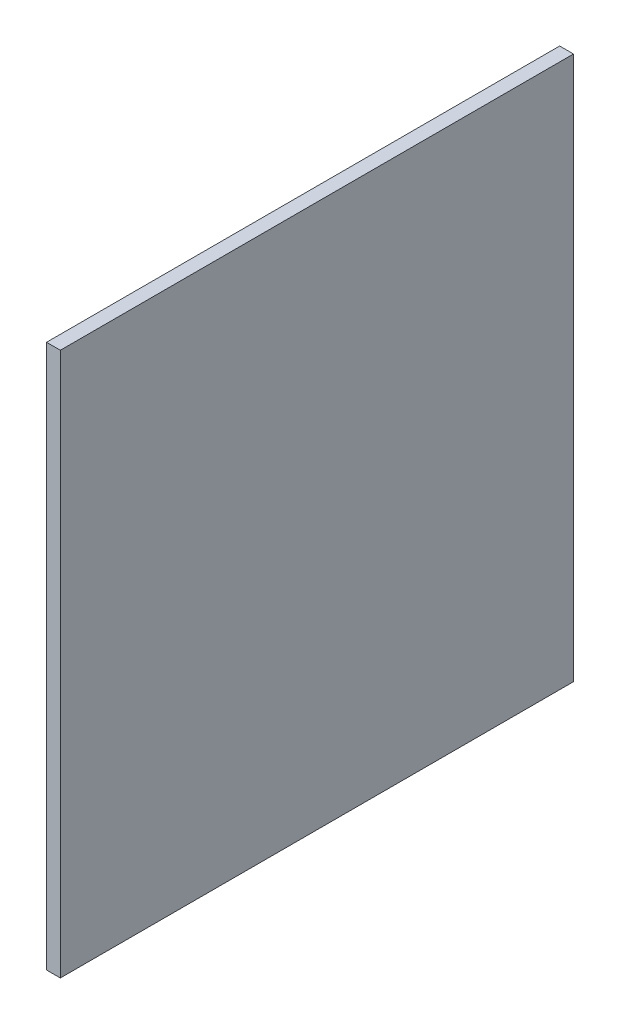
SolidWorks part; units mm, degrees
ref_plane "Front" through (0, 0, 0) normal (0, 0, 1) x (1, 0, 0)
ref_plane "Top" through (0, 0, 0) normal (0, 1, 0) x (1, 0, 0)
ref_plane "Right" through (0, 0, 0) normal (1, 0, 0) x (0, 0, -1)
sketch "Sketch1" plane through (0, 0, 0) normal (1, 0, 0) x (0, 0, -1)
  line L1 (0, 0) -> (353.95, 0)
  line L2 (0, 0) -> (0, 375)
  line L3 (0, 375) -> (353.95, 375)
  line L4 (353.95, 0) -> (353.95, 375)
  dimension "D1" = 375
  dimension "D2" = 353.95
extrude "Boss-Extrude1" add sketch "Sketch1" along normal blind 9.525
